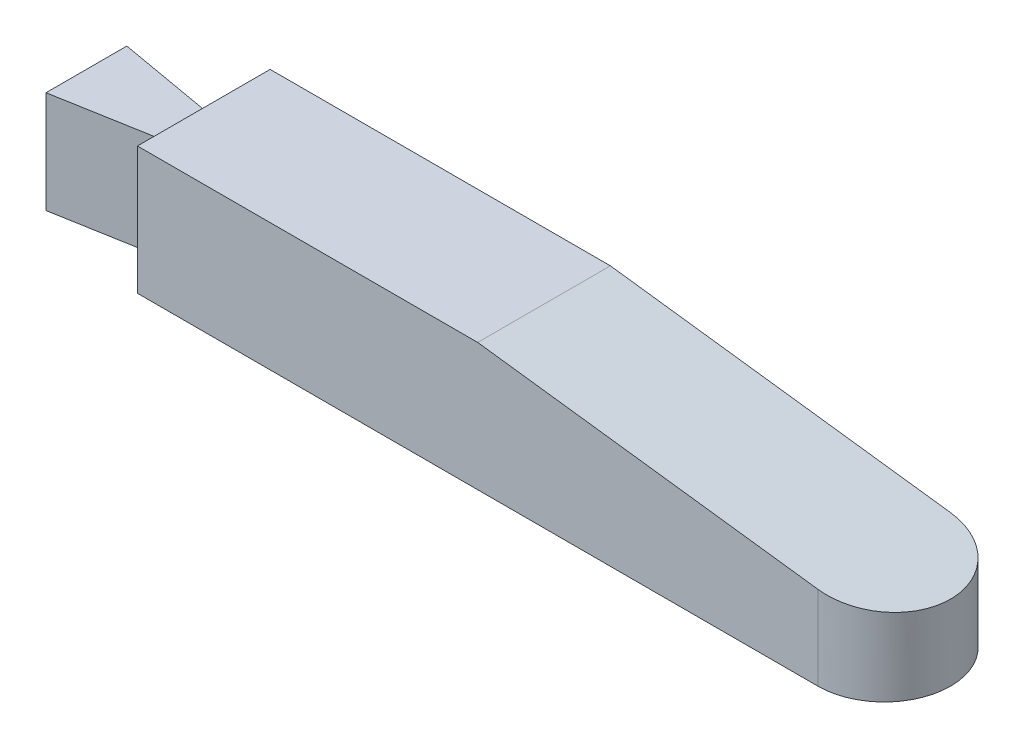
SolidWorks part; units mm, degrees
ref_plane "Front Plane" through (0, 0, 0) normal (0, 0, 1) x (1, 0, 0)
ref_plane "Top Plane" through (0, 0, 0) normal (0, 1, 0) x (1, 0, 0)
ref_plane "Right Plane" through (0, 0, 0) normal (1, 0, 0) x (0, 0, -1)
sketch "Sketch2" plane through (0, 0, 0) normal (0, 1, 0) x (1, 0, 0)
  line L10 (0, -13.9276) -> (0, -25.6964) construction
  line L29 (-35.052, -7.747) -> (-35.052, -31.877)
  line L30 (-35.052, -7.747) -> (0, -13.9276)
  line L31 (-35.052, -31.877) -> (0, -25.6964)
  line L32 (0, 0) -> (203.2, 0)
  line L33 (0, -39.624) -> (203.2, -39.624)
  line L35 (0, 0) -> (0, -13.9276)
  line L36 (0, -39.624) -> (0, -25.6964)
  line L37 (-35.052, -19.812) -> (0, -19.812) construction
  arc A5 (203.2, 0) -> (203.2, -39.624) centre (203.2, -19.812) cw
  dimension "D4" = 13.9276
  dimension "D5" = 39.624
  dimension "D3" = 24.13
  dimension "D7" = 13.9276
  dimension "D1" = 35.052
  dimension "D2" = 80
  dimension "D6" = 203.2
extrude "Boss-Extrude1" add sketch "Sketch2" along normal blind 38.1
sketch "Sketch3" plane through (0, 38.1, 0) normal (0, 1, 0) x (1, 0, 0)
  line L0 (-35.052, -7.747) -> (-35.052, -31.877)
  line L1 (-35.052, -31.877) -> (0, -25.6964)
  line L2 (0, -25.6964) -> (0, -13.9276)
  line L3 (0, -13.9276) -> (-35.052, -7.747)
extrude "Cut-Extrude1" cut sketch "Sketch3" against normal blind 7.62
sketch "Sketch5" plane through (0, 0, 39.624) normal (0, 0, 1) x (1, 0, 0)
  line L5 (101.6, 38.1) -> (223.012, 22.5197)
  line L6 (0, 38.1) -> (203.2, 38.1) construction
  line L7 (223.012, 0) -> (223.012, 38.1) construction
  line L8 (223.012, 22.5197) -> (223.012, 38.1)
  line L9 (223.012, 38.1) -> (101.6, 38.1)
  dimension "D1" = 7.313
extrude "Cut-Extrude4" cut sketch "Sketch5" against normal blind 39.624
